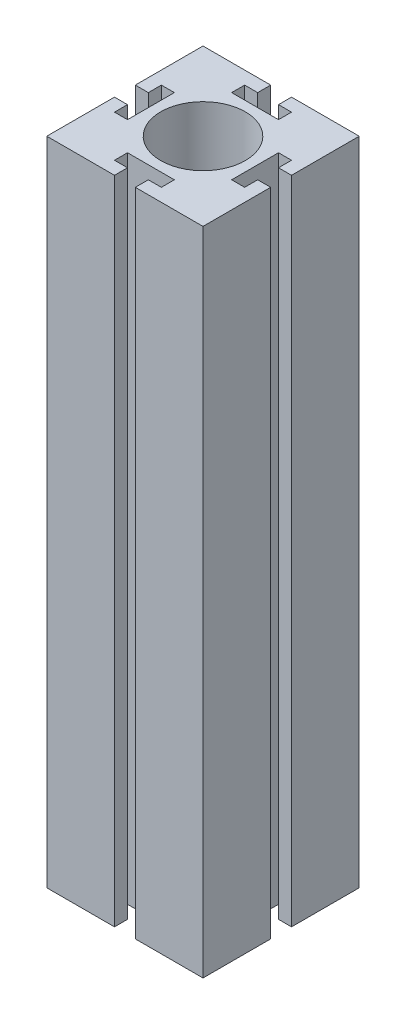
SolidWorks part; units mm, degrees
ref_plane "Plan de face" through (0, 0, 0) normal (0, 0, 1) x (1, 0, 0)
ref_plane "Plan de dessus" through (0, 0, 0) normal (0, 1, 0) x (1, 0, 0)
ref_plane "Plan de droite" through (0, 0, 0) normal (1, 0, 0) x (0, 0, -1)
sketch "Esquisse1" plane through (0, 0, 0) normal (0, 1, 0) x (1, 0, 0)
  line L1 (-6, 6) -> (6, 6)
  line L2 (-6, 6) -> (-6, -6)
  line L3 (-6, -6) -> (6, -6)
  line L4 (6, 6) -> (6, -6)
  dimension "D1" = 12
  dimension "D2" = 12
  dimension "D3" = 6
  dimension "D4" = 6
extrude "Boss.-Extru.1" add sketch "Esquisse1" along normal blind 50
sketch "Esquisse2" plane through (0, 50, 0) normal (0, 1, 0) x (1, 0, 0)
  line L0 (-5, -0.8) -> (-5, -1.8)
  line L1 (-6, 0.8) -> (-5, 0.8)
  line L2 (-6, 0.8) -> (-6, -0.8)
  line L3 (-6, -0.8) -> (-5, -0.8)
  line L5 (-5, 1.8) -> (-4, 1.8)
  line L6 (-5, 1.8) -> (-5, 0.8)
  line L7 (-5, -1.8) -> (-4, -1.8)
  line L8 (-4, 1.8) -> (-4, -1.8)
  line L9 (-6, 6) -> (-6, -6) construction
  line L10 (1.8, 5) -> (1.8, 4)
  line L11 (1.8, 4) -> (-1.8, 4)
  line L12 (-1.8, 5) -> (-1.8, 4)
  line L13 (-0.8, 5) -> (-1.8, 5)
  line L14 (-0.8, 6) -> (-0.8, 5)
  line L15 (0.8, 6) -> (-0.8, 6)
  line L16 (0.8, 6) -> (0.8, 5)
  line L17 (1.8, 5) -> (0.8, 5)
  line L18 (5, -1.8) -> (4, -1.8)
  line L19 (4, -1.8) -> (4, 1.8)
  line L20 (5, 1.8) -> (4, 1.8)
  line L21 (5, 0.8) -> (5, 1.8)
  line L22 (6, 0.8) -> (5, 0.8)
  line L23 (6, -0.8) -> (6, 0.8)
  line L24 (6, -0.8) -> (5, -0.8)
  line L25 (5, -1.8) -> (5, -0.8)
  line L26 (-1.8, -5) -> (-1.8, -4)
  line L27 (-1.8, -4) -> (1.8, -4)
  line L28 (1.8, -5) -> (1.8, -4)
  line L29 (0.8, -5) -> (1.8, -5)
  line L30 (0.8, -6) -> (0.8, -5)
  line L31 (-0.8, -6) -> (0.8, -6)
  line L32 (-0.8, -6) -> (-0.8, -5)
  line L33 (-1.8, -5) -> (-0.8, -5)
  point P38 (0, 0)
  dimension "D1" = 1.6
  dimension "D2" = 1
  dimension "D3" = 1
  dimension "D4" = 0
  dimension "D5" = 0.8
  dimension "D6" = 1
  dimension "D7" = 2
  dimension "D8" = 4
extrude "Enlèv. mat.-Extru.1" cut sketch "Esquisse2" against normal up to vertex (50 mm away) up to point (0, 0, 0)
sketch "Esquisse3" plane through (0, 50, 0) normal (0, 1, 0) x (1, 0, 0)
  circle A0 centre (0, 0) radius 3.25
  dimension "D1" = 6.5
extrude "Enlèv. mat.-Extru.2" cut sketch "Esquisse3" against normal blind 47
sketch "Esquisse4" plane through (0, 3, 0) normal (0, 1, 0) x (1, 0, 0)
  circle A0 centre (0, 0) radius 1.5
  dimension "D1" = 3
extrude "Enlèv. mat.-Extru.3" cut sketch "Esquisse4" against normal up to surface (3 mm away) up to face at (0, 0, 0)
